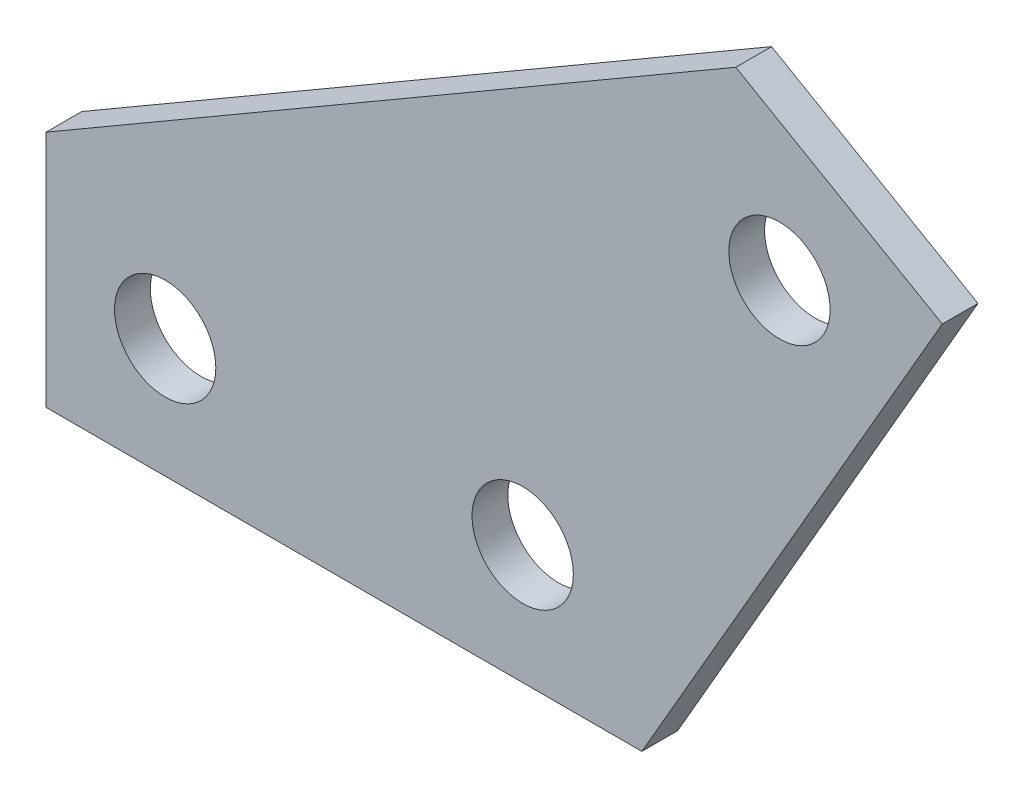
SolidWorks part; units mm, degrees
ref_plane "Front Plane" through (0, 0, 0) normal (0, 0, 1) x (1, 0, 0)
ref_plane "Top Plane" through (0, 0, 0) normal (0, 1, 0) x (1, 0, 0)
ref_plane "Right Plane" through (0, 0, 0) normal (1, 0, 0) x (0, 0, -1)
sketch "Sketch1" plane through (0, 0, 0) normal (0, 0, 1) x (1, 0, 0)
  line L0 (40, 10) -> (50, 10) construction
  line L1 (0, 0) -> (250, 0) construction
  line L2 (0, 0) -> (0, 60) construction
  line L3 (0, 60) -> (250, 60) construction
  line L4 (250, 0) -> (250, 60) construction
  line L5 (0, 0) -> (50, 0) construction
  line L6 (0, 0) -> (0, 20) construction
  line L7 (0, 20) -> (50, 20) construction
  line L8 (50, 0) -> (50, 20) construction
  line L9 (40, 10) -> (10, 10) construction
  line L10 (10, 10) -> (0, 10) construction
  line L11 (50, 0) -> (75.2073, 43.6603)
  line L12 (75.2073, 43.6603) -> (57.8868, 53.6603)
  line L13 (57.8868, 53.6603) -> (38.453, 20) construction
  line L14 (38.453, 20) -> (0, 20) construction
  line L15 (0, 20) -> (0, 0)
  line L16 (0, 0) -> (50, 0)
  line L17 (66.547, 48.6603) -> (61.547, 40) construction
  line L18 (0, 20) -> (57.8868, 53.6603)
  circle A0 centre (40, 10) radius 4.25
  circle A1 centre (10, 10) radius 4.25
  circle A2 centre (61.547, 40) radius 4.25
  dimension "D4" = 10
  dimension "D9" = 8.5
  dimension "D1" = 60
  dimension "D2" = 250
  dimension "D3" = 20
  dimension "D5" = 30
  dimension "D6" = 10
  dimension "D7" = 60
  dimension "D8" = 20
  dimension "D10" = 20
extrude "Boss-Extrude1" add sketch "Sketch1" along normal blind 3
